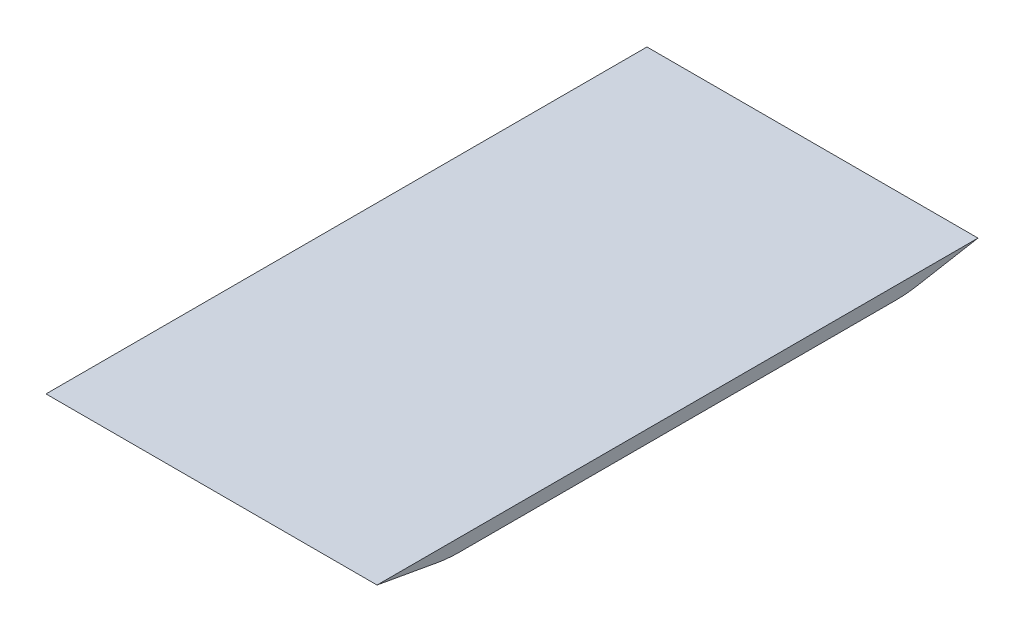
SolidWorks part; units mm, degrees
ref_plane "Front Plane" through (0, 0, 0) normal (0, 0, 1) x (1, 0, 0)
ref_plane "Top Plane" through (0, 0, 0) normal (0, 1, 0) x (1, 0, 0)
ref_plane "Right Plane" through (0, 0, 0) normal (1, 0, 0) x (0, 0, -1)
sketch "Sketch1" plane through (0, 0, 0) normal (1, 0, 0) x (0, 0, -1)
  line L0 (0, 0) -> (236, 0)
  line L1 (236, 0) -> (208, -5)
  line L2 (208, -5) -> (28, -5)
  line L3 (28, -5) -> (0, 0)
  point P3 (118, 0)
  dimension "D1" = 180
  dimension "D2" = 28
  dimension "D3" = 28
  dimension "D4" = 5
extrude "Boss-Extrude1" add sketch "Sketch1" along normal blind 130
fillet "Fillet1" radius 50 2 edges at (65, -5, -28) (65, -5, -208)
